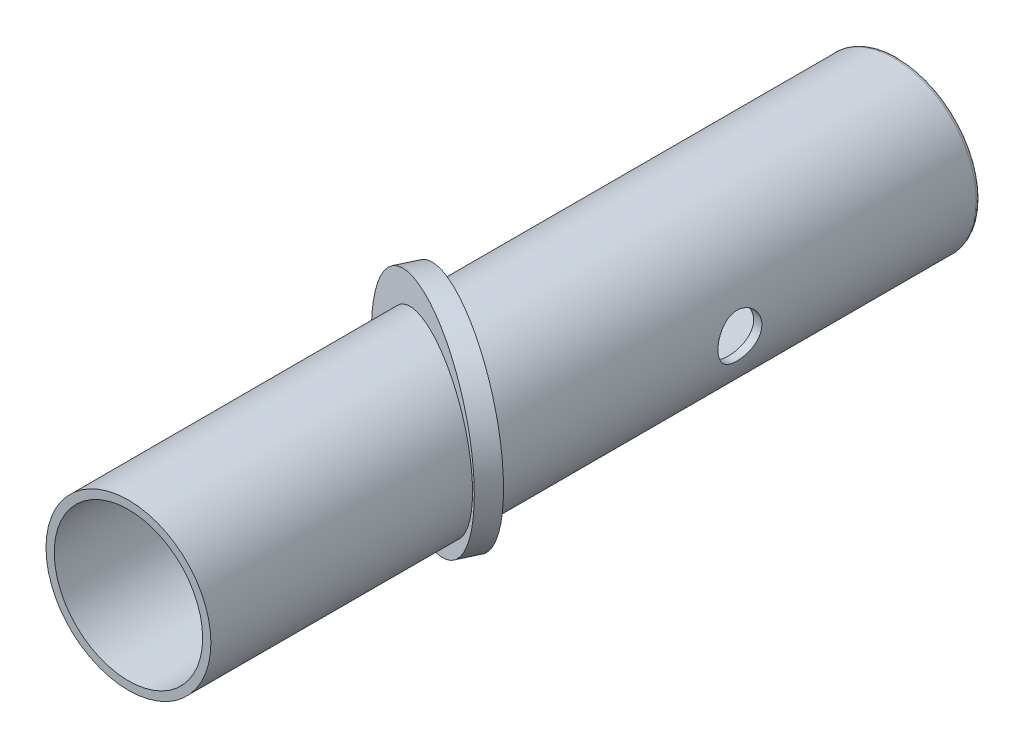
SolidWorks part; units mm, degrees
ref_plane "Front Plane" through (0, 0, 0) normal (0, 0, 1) x (1, 0, 0)
ref_plane "Top Plane" through (0, 0, 0) normal (0, 1, 0) x (1, 0, 0)
ref_plane "Right Plane" through (0, 0, 0) normal (1, 0, 0) x (0, 0, -1)
sketch "Sketch1" plane through (0, 0, 0) normal (0, 0, 1) x (1, 0, 0)
  circle A0 centre (0, 0) radius 7.5
  circle A1 centre (0, 0) radius 6.75
  dimension "D1" = 15
  dimension "D2" = 13.5
extrude "Boss-Extrude1" add sketch "Sketch1" along normal blind 70
ref_plane "Plane1" through (0, 0, 45) normal (0, 0, 1) x (1, 0, 0)
ref_plane "Plane2" through (0, 0, 37) normal (0, 0, 1) x (1, 0, 0)
sketch "Sketch2" plane through (0, 0, 37) normal (0, 0, 1) x (1, 0, 0)
  line L0 (-7.5, 10.088) -> (-7.5, -7.8649) construction
  dimension "D1" = 7.5
ref_plane "Plane3" through (-15.5114, 0, 33.2642) normal (-0.4226, 0, 0.9063) x (0, -1, 0)
fillet "Fillet2" radius 0.37 2 edges at (6.75, 0, 0) (7.5, 0, 0)
sketch "Sketch8" plane through (-15.5114, 0, 33.2642) normal (-0.4226, 0, 0.9063) x (0, -1, 0)
  circle A0 centre (0, 16.9812) radius 9.6785
extrude "Boss-Extrude6" add sketch "Sketch8" along normal blind 2
sketch "Sketch9" plane through (0, 0, 0) normal (0, 0, 1) x (1, 0, 0)
  circle A0 centre (0, 0) radius 6.75 construction
  circle A1 centre (0, 0) radius 6.75
extrude "Cut-Extrude2" cut sketch "Sketch9" along normal blind 72
sketch "Sketch10" plane through (0, 0, 0) normal (1, 0, 0) x (0, 0, -1)
  line L0 (30.3051, 0) -> (-111.1934, 0) construction
  circle A0 centre (-21.8752, 0) radius 2
  dimension "D1" = 4
extrude "Cut-Extrude3" cut sketch "Sketch10" along normal blind 10
